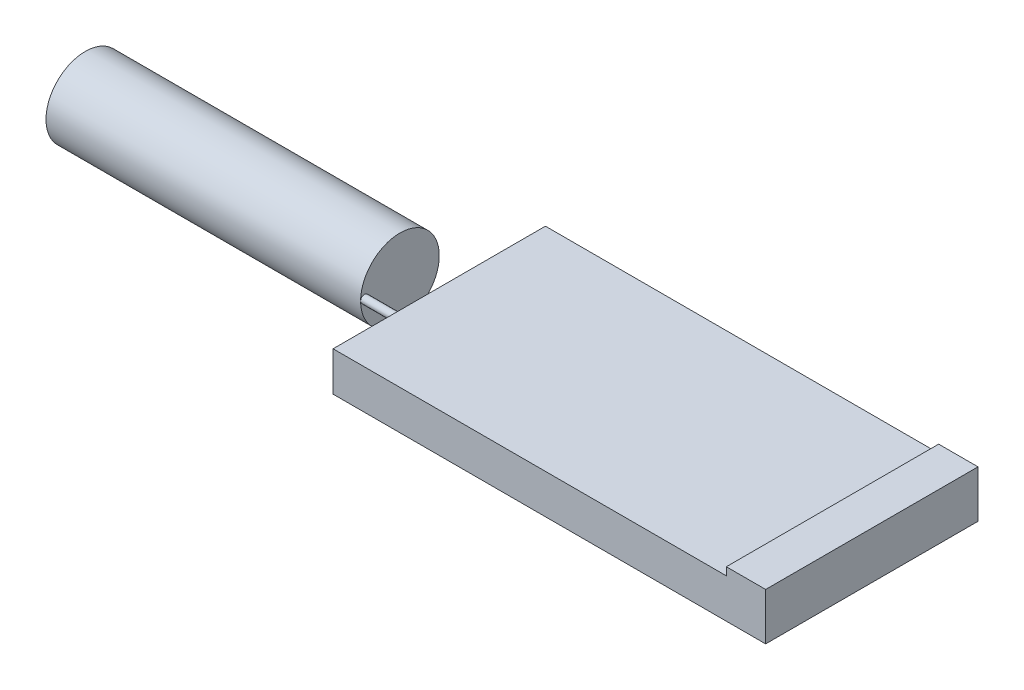
SolidWorks part; units mm, degrees
ref_plane "Спереди" through (0, 0, 0) normal (0, 0, 1) x (1, 0, 0)
ref_plane "Сверху" through (0, 0, 0) normal (0, 1, 0) x (1, 0, 0)
ref_plane "Справа" through (0, 0, 0) normal (1, 0, 0) x (0, 0, -1)
other "Configuration Table"
sketch "Эскиз1" plane through (0, 0, 0) normal (0, 1, 0) x (1, 0, 0)
  line L1 (-13.75, -6.75) -> (13.75, -6.75)
  line L2 (-13.75, -6.75) -> (-13.75, 6.75)
  line L3 (-13.75, 6.75) -> (13.75, 6.75)
  line L4 (13.75, -6.75) -> (13.75, 6.75)
  line L5 (-13.75, -6.75) -> (13.75, 6.75) construction
  line L6 (-13.75, 6.75) -> (13.75, -6.75) construction
  point P0 (0, 0)
  dimension "D1" = 13.5
  dimension "D2" = 27.5
extrude "Бобышка-Вытянуть1" add sketch "Эскиз1" along normal blind 2.5
sketch "Эскиз2" plane through (0, 0, 0) normal (0, -1, 0) x (1, 0, 0)
  line L1 (13.75, 6.75) -> (11.25, 6.75)
  line L2 (13.75, 6.75) -> (13.75, -6.75)
  line L3 (13.75, -6.75) -> (11.25, -6.75)
  line L4 (13.75, -6.75) -> (13.75, 6.75)
  line L5 (13.75, 6.75) -> (-13.75, 6.75)
  line L6 (-13.75, 6.75) -> (-13.75, -6.75)
  line L7 (-13.75, -6.75) -> (13.75, -6.75)
  line L8 (13.75, -6.75) -> (13.75, 6.75)
  line L9 (13.75, 6.75) -> (-13.75, 6.75)
  line L10 (-13.75, 6.75) -> (-13.75, -6.75)
  line L11 (-13.75, -6.75) -> (13.75, -6.75)
  line L12 (11.25, 6.75) -> (11.25, -6.75)
  line M9 (13.75, -6.75) -> (13.75, 6.75)
  line M10 (13.75, 6.75) -> (-13.75, 6.75)
  line M12 (-13.75, -6.75) -> (13.75, -6.75)
  dimension "D2" = 2.5
  dimension "D1" = 0
extrude "Бобышка-Вытянуть2" add sketch "Эскиз2" against normal blind 3 contours L12 M10 M12 M9
sketch "Эскиз3" plane through (-13.75, 0, 0) normal (-1, 0, 0) x (0, 0, 1)
  line L0 (-6.75, 0) -> (6.75, 0) construction
  line L1 (6.75, 2.5) -> (6.75, 0) construction
  circle A0 centre (1.75, 1.25) radius 0.25
  point P2 (0, 0)
  point P5 (0, 0)
  point P8 (2.5404, 0.4026)
  point P9 (2.0351, 0.306)
  dimension "D1" = 0.5
  dimension "D2" = 1.25
  dimension "D3" = 5
extrude "Бобышка-Вытянуть3" add sketch "Эскиз3" along normal blind 3
sketch "Эскиз4" plane through (-16.75, 0, 0) normal (-1, 0, 0) x (0, 0, 1)
  circle A0 centre (-0.5, 1.25) radius 2.5
  circle A1 centre (1.75, 1.25) radius 0.25
  circle A2 centre (1.75, 1.25) radius 0.25
  point P5 (1.0537, 1.25)
  point P6 (0, 1.25)
  circle M3 centre (1.75, 1.25) radius 0.25
  dimension "D2" = 5
  dimension "D1" = 0
extrude "Бобышка-Вытянуть5" add sketch "Эскиз4" along normal blind 20 contours M3 | A0 M3
